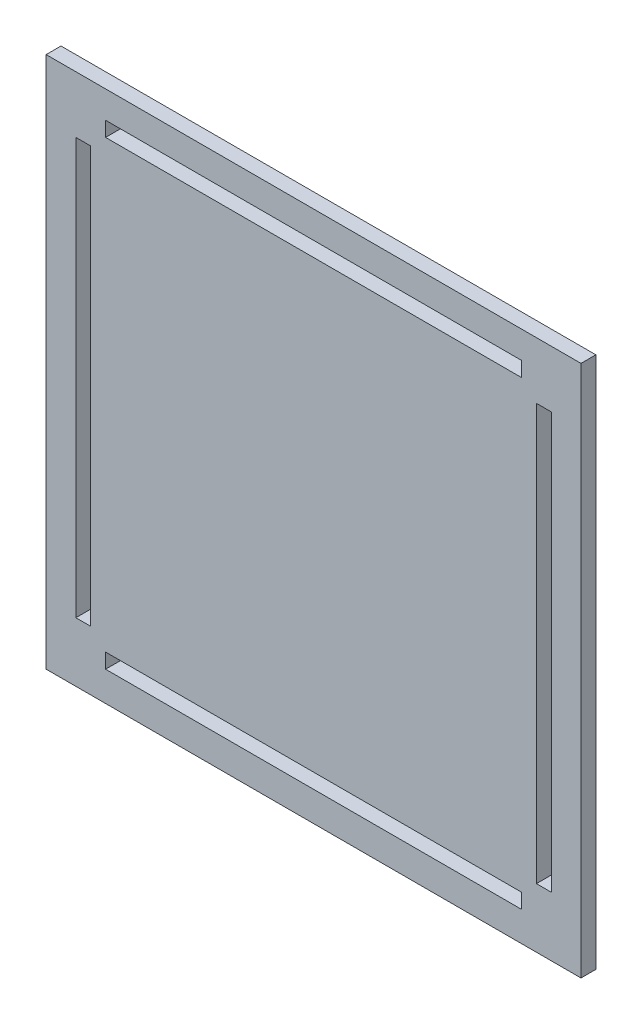
SolidWorks part; units mm, degrees
ref_plane "Plan de face" through (0, 0, 0) normal (0, 0, 1) x (1, 0, 0)
ref_plane "Plan de dessus" through (0, 0, 0) normal (0, 1, 0) x (1, 0, 0)
ref_plane "Plan de droite" through (0, 0, 0) normal (1, 0, 0) x (0, 0, -1)
sketch "Esquisse1" plane through (0, 0, 0) normal (0, 0, 1) x (1, 0, 0)
  line L0 (70, 80) -> (70, 75)
  line L1 (-90, 89.1406) -> (90, 89.1406)
  line L2 (-90, 89.1406) -> (-90, -90)
  line L3 (-90, -90) -> (90, -90)
  line L4 (90, 89.1406) -> (90, -90)
  line L9 (-80, 70) -> (-75, 70)
  line L10 (-80, 70) -> (-80, -70)
  line L11 (-80, -70) -> (-75, -70)
  line L12 (-75, 70) -> (-75, -70)
  line L13 (70, 80) -> (-70, 80)
  line L14 (-70, 80) -> (-70, 75)
  line L15 (70, 75) -> (-70, 75)
  line L16 (80, -70) -> (75, -70)
  line L17 (80, -70) -> (80, 70)
  line L18 (80, 70) -> (75, 70)
  line L19 (75, -70) -> (75, 70)
  line L20 (-70, -80) -> (-70, -75)
  line L21 (-70, -80) -> (70, -80)
  line L22 (70, -80) -> (70, -75)
  line L23 (-70, -75) -> (70, -75)
  point P24 (0, 0)
  dimension "D5" = 4
extrude "Boss.-Extru.1" add sketch "Esquisse1" along normal blind 5
